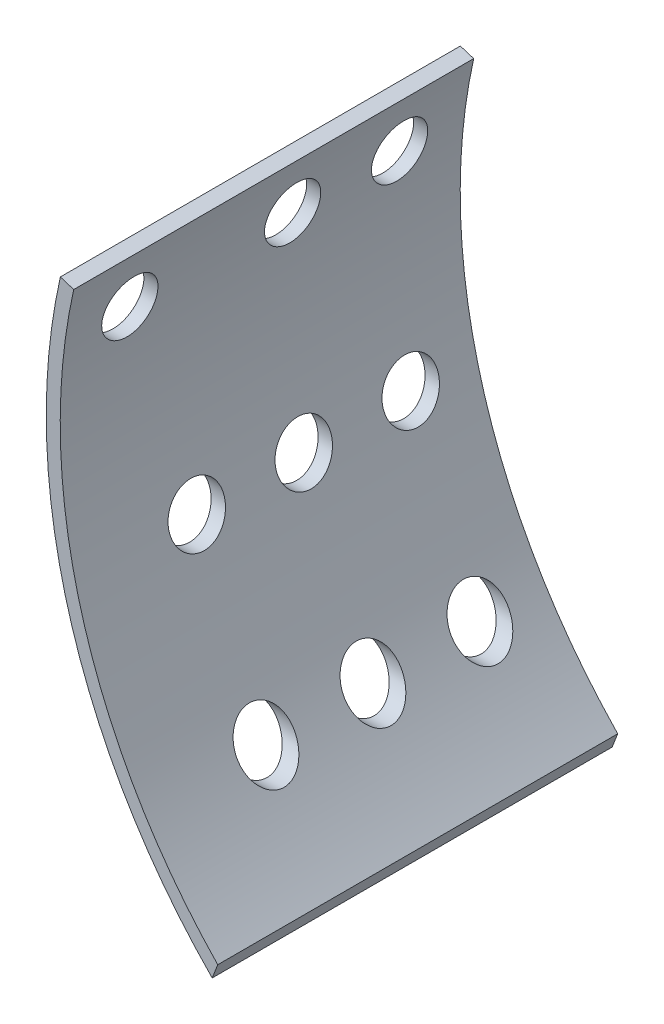
SolidWorks part; units mm, degrees
material "AISI 1020"
ref_plane "Ön Düzlem" through (0, 0, 0) normal (0, 0, 1) x (1, 0, 0)
ref_plane "Üst Düzlem" through (0, 0, 0) normal (0, 1, 0) x (1, 0, 0)
ref_plane "Sağ Düzlem" through (0, 0, 0) normal (1, 0, 0) x (0, 0, -1)
sketch "Model" plane through (0, 0, 0) normal (0, 0, 1) x (1, 0, 0)
  line L0 (2607.29, 2081.1259) -> (2592.9332, 2085.655)
  line L1 (2756.1391, 1514.5545) -> (2762.1125, 1529.913)
  arc A0 (2607.29, 2081.1259) -> (2762.1125, 1529.913) centre (3197.094, 1949.4384) ccw
  arc A1 (2592.9332, 2085.655) -> (2756.1391, 1514.5545) centre (3197.094, 1949.4384) ccw
extrude "Yükseklik-Ekstrüzyon1" add sketch "Model" along normal blind 430
sketch "Sketch1" plane through (0, 0, 0) normal (1, 0, 0) x (0, 0, -1)
  line L0 (-430, 2085.655) -> (0, 2085.655) construction
  line L1 (0, 1514.5545) -> (0, 2085.655) construction
  line L2 (-430, 2085.655) -> (-430, 1514.5545) construction
  circle A1 centre (-360, 2025.655) radius 30
  circle A2 centre (-185, 2025.655) radius 30
  circle A3 centre (-70, 2025.655) radius 30
  circle A4 centre (-300, 1808.1527) radius 30
  circle A5 centre (-185, 1808.1527) radius 30
  circle A6 centre (-70, 1808.1527) radius 30
  circle A7 centre (-300, 1630.7622) radius 30
  circle A8 centre (-185, 1630.7622) radius 30
  circle A9 centre (-70, 1630.7622) radius 30
  dimension "D1" = 60
  dimension "D2" = 60
  dimension "D3" = 60
  dimension "D5" = 60
  dimension "D6" = 60
  dimension "D8" = 185
  dimension "D10" = 60
  dimension "D11" = 60
  dimension "D12" = 60
  dimension "D13" = 60
  dimension "D14" = 60
  dimension "D15" = 60
  dimension "D4" = 60
  dimension "D7" = 70
  dimension "D9" = 70
extrude "Cut-Extrude3" cut sketch "Sketch1" along normal through all contours A2 | A1 | A3 | A4 | A5 | A6 | A7 | A8 | A9
